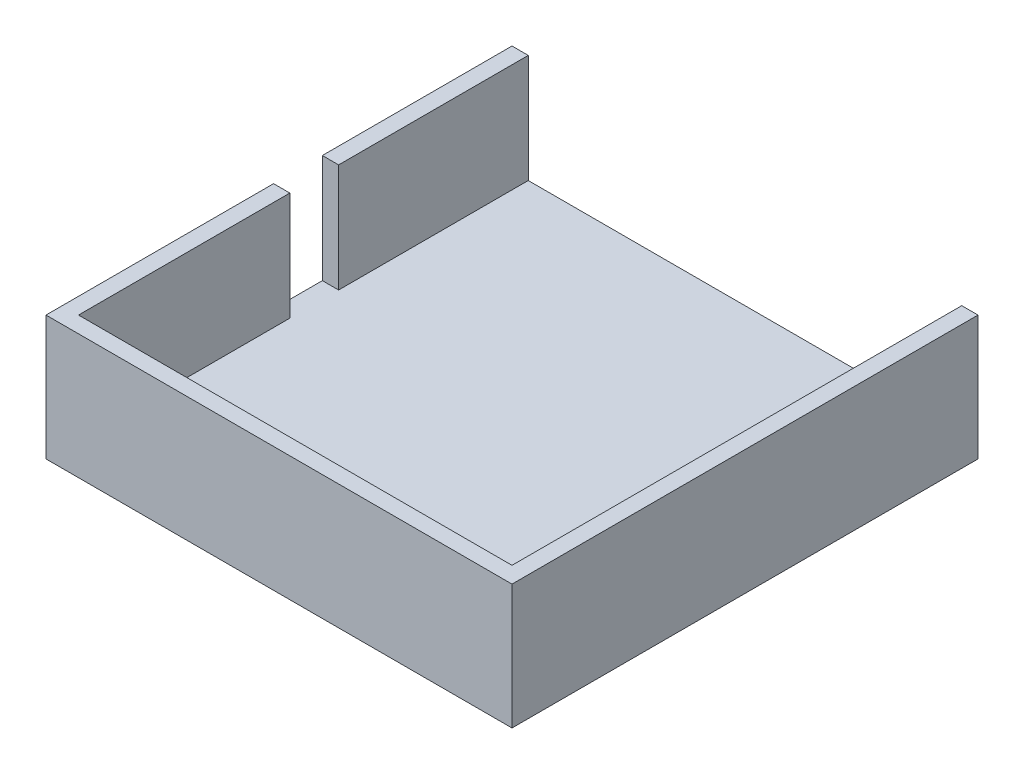
SolidWorks part; units mm, degrees
ref_plane "Front Plane" through (0, 0, 0) normal (0, 0, 1) x (1, 0, 0)
ref_plane "Top Plane" through (0, 0, 0) normal (0, 1, 0) x (1, 0, 0)
ref_plane "Right Plane" through (0, 0, 0) normal (1, 0, 0) x (0, 0, -1)
sketch "Sketch1" plane through (0, 0, 0) normal (0, 1, 0) x (1, 0, 0)
  line L1 (-49.4944, 47.0801) -> (36.5056, 47.0801)
  line L2 (-49.4944, 47.0801) -> (-49.4944, -38.9199)
  line L3 (-49.4944, -38.9199) -> (36.5056, -38.9199)
  line L4 (36.5056, 47.0801) -> (36.5056, -38.9199)
  dimension "D1" = 86
  dimension "D2" = 86
extrude "Boss-Extrude1" add sketch "Sketch1" along normal blind 23
shell "Shell1" thickness 3
sketch "Sketch2" plane through (-49.4944, 0, 0) normal (-1, 0, 0) x (0, 0, 1)
  line L0 (-47.0801, 23) -> (38.9199, 23) construction
  line L1 (-12.0801, 23) -> (-3.0801, 23)
  line L2 (-12.0801, 23) -> (-12.0801, 3)
  line L3 (-12.0801, 3) -> (-3.0801, 3)
  line L4 (-3.0801, 23) -> (-3.0801, 3)
  line L6 (-47.0801, 23) -> (-47.0801, 0) construction
  line L7 (38.9199, 23) -> (38.9199, 0) construction
  dimension "D1" = 20
  dimension "D2" = 9
  dimension "D3" = 35
  dimension "D4" = 42
extrude "Cut-Extrude1" cut sketch "Sketch2" against normal blind 3 contours L2 L1 L4 L3
